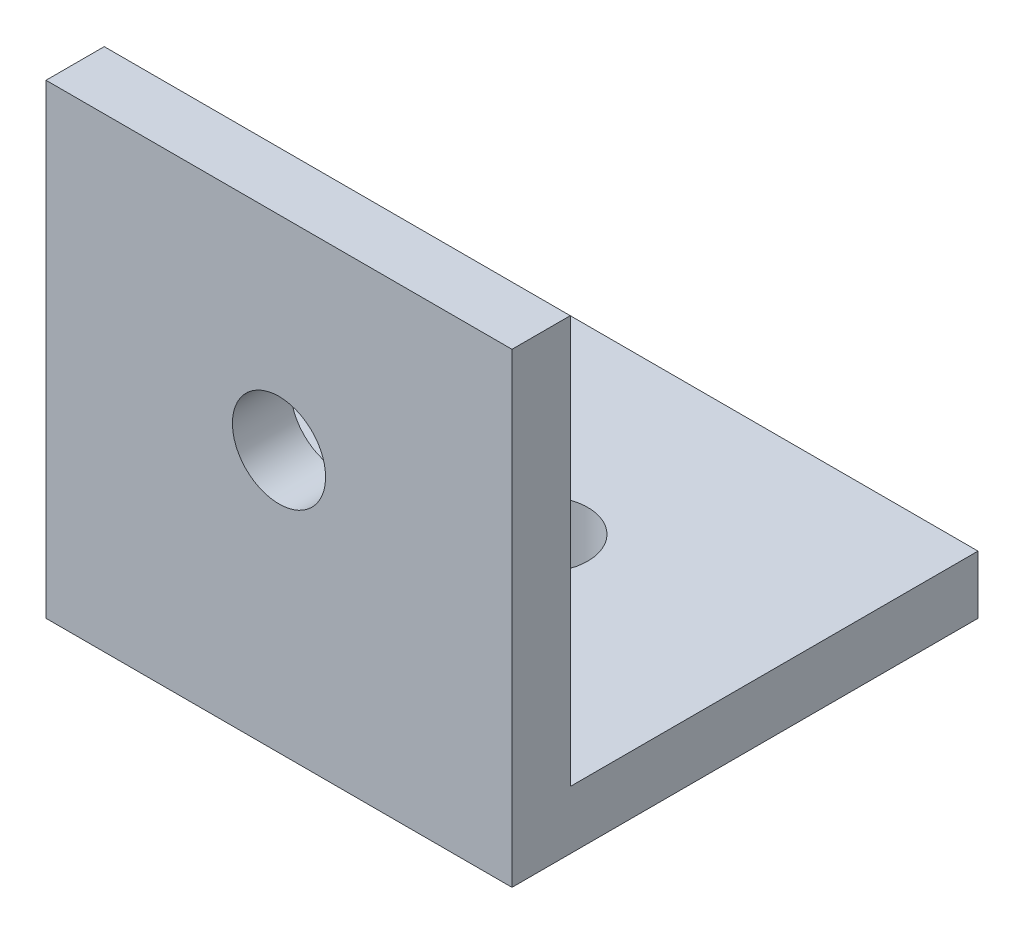
SolidWorks part; units mm, degrees
ref_plane "Front Plane" through (0, 0, 0) normal (0, 0, 1) x (1, 0, 0)
ref_plane "Top Plane" through (0, 0, 0) normal (0, 1, 0) x (1, 0, 0)
ref_plane "Right Plane" through (0, 0, 0) normal (1, 0, 0) x (0, 0, -1)
sketch "Sketch1" plane through (0, 0, 0) normal (1, 0, 0) x (0, 0, -1)
  line L0 (0, 0) -> (0, 25.4)
  line L1 (0, 25.4) -> (3.175, 25.4)
  line L2 (3.175, 25.4) -> (3.175, 3.175)
  line L3 (3.175, 3.175) -> (25.4, 3.175)
  line L4 (25.4, 3.175) -> (25.4, 0)
  line L5 (25.4, 0) -> (0, 0)
  dimension "D1" = 25.4
  dimension "D2" = 25.4
  dimension "D3" = 3.175
  dimension "D4" = 3.175
extrude "Boss-Extrude1" add sketch "Sketch1" along normal blind 25.4
sketch "Sketch2" plane through (0, 3.175, 0) normal (0, 1, 0) x (1, 0, 0)
  line L0 (25.4, 14.2875) -> (0, 14.2875) construction
  line L1 (25.4, 25.4) -> (25.4, 3.175) construction
  line L2 (0, 25.4) -> (0, 3.175) construction
  circle A0 centre (12.7, 14.2875) radius 2.54
  dimension "D1" = 5.08
extrude "Cut-Extrude1" cut sketch "Sketch2" against normal through all
sketch "Sketch3" plane through (0, 0, -3.175) normal (0, 0, -1) x (-1, 0, 0)
  line L0 (-25.4, 14.2875) -> (0, 14.2875) construction
  line L1 (-25.4, 3.175) -> (-25.4, 25.4) construction
  line L2 (0, 3.175) -> (0, 25.4) construction
  circle A0 centre (-12.7, 14.2875) radius 2.54
  dimension "D1" = 5.08
extrude "Cut-Extrude2" cut sketch "Sketch3" against normal through all
